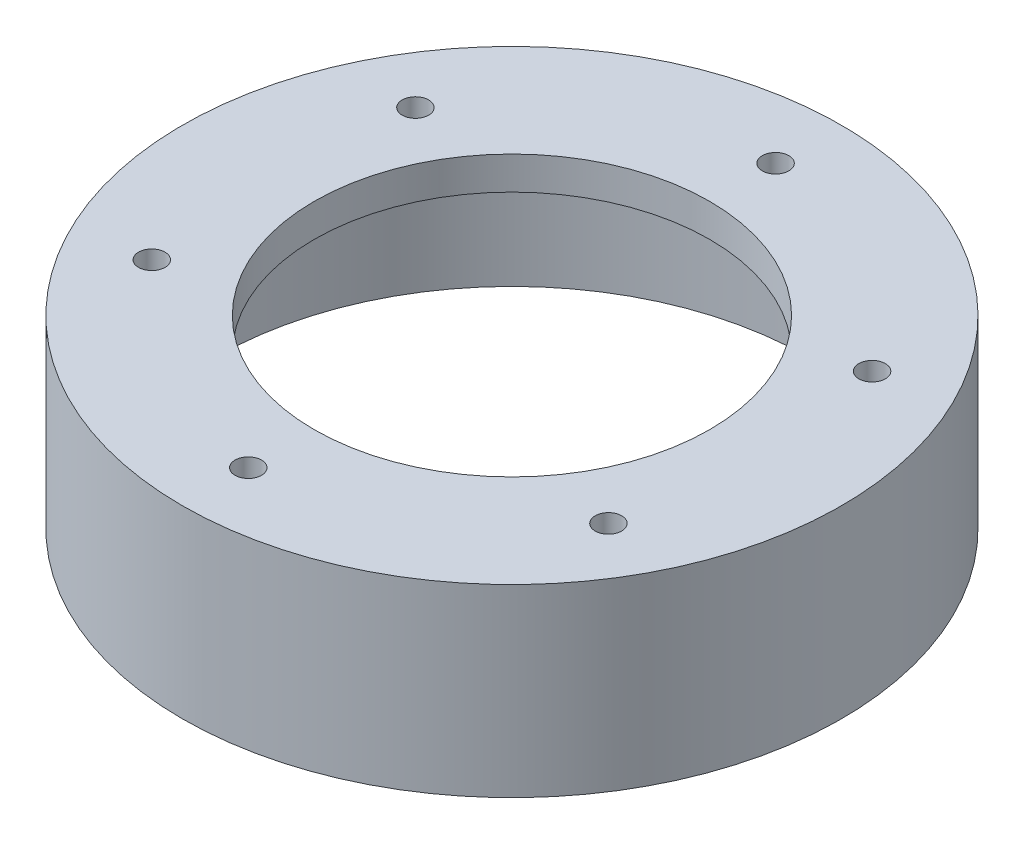
SolidWorks part; units mm, degrees
material "6061 Alloy"
ref_plane "Front Plane" through (0, 0, 0) normal (0, 0, 1) x (1, 0, 0)
ref_plane "Top Plane" through (0, 0, 0) normal (0, 1, 0) x (1, 0, 0)
ref_plane "Right Plane" through (0, 0, 0) normal (1, 0, 0) x (0, 0, -1)
sketch "Sketch1" plane through (0, 0, 0) normal (0, 1, 0) x (1, 0, 0)
  circle A0 centre (0, 0) radius 63.5
  circle A1 centre (0, 0) radius 38.1
  dimension "D1" = 76.2
  dimension "D2" = 127
extrude "Boss-Extrude1" add sketch "Sketch1" along normal blind 35.56
sketch "Sketch2" plane through (0, 0, 0) normal (0, -1, 0) x (1, 0, 0)
  circle A0 centre (0, 0) radius 57.15
  dimension "D1" = 114.3
extrude "Cut-Extrude1" cut sketch "Sketch2" against normal blind 29.21
hole_wizard "#10 Clearance Hole1" positions "Sketch3" profile "Sketch4" hole size "#10" standard "ANSI Inch" end condition up to next
sketch "Sketch3" plane through (0, 35.56, 0) normal (0, 1, 0) x (1, 0, 0)
  point P0 (0, 50.8)
  dimension "D1" = 50.8
sketch "Sketch4" plane through (0, 35.56, -50.8) normal (1, 0, 0) x (0, 0, 1)
  line L0 (0, 0) -> (0, 6.351)
  line L1 (0, 6.351) -> (2.5527, 6.351)
  line L2 (2.5527, 6.351) -> (2.5527, 0)
  line L5 (2.5527, 0) -> (0, 0)
  line L11 (0, -6.35) -> (0, 107.95) construction
  dimension "Thru Hole Dia." = 5.1054
  dimension "Thru Hole Depth" = 6.351
pattern_circular "CirPattern1" count 6 over 360 about axis through (0, 0, 0) along (0, 1, 0) of "#10 Clearance Hole1"
